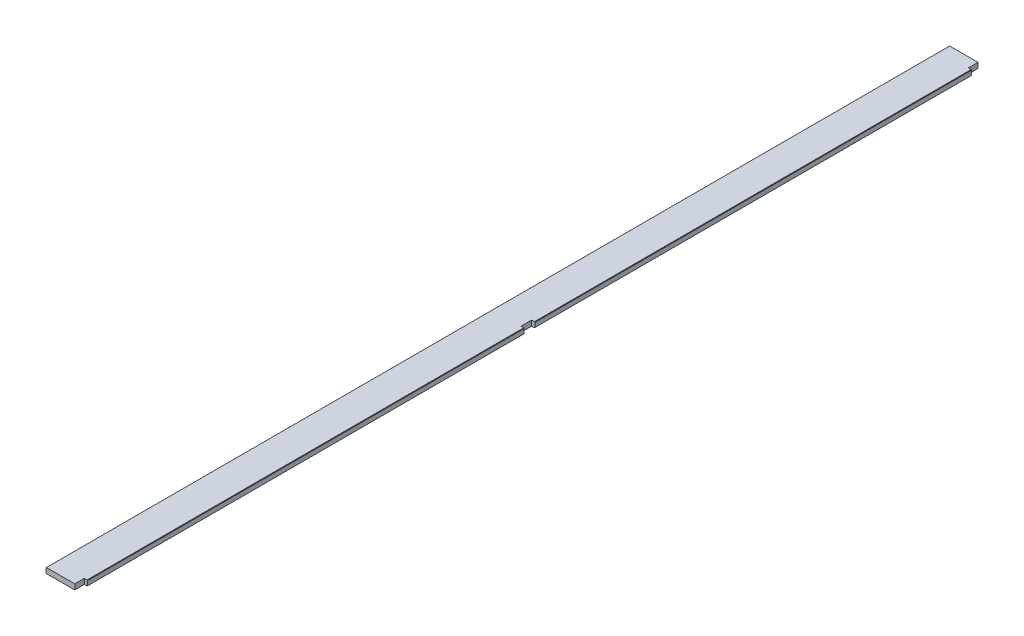
SolidWorks part; units mm, degrees
ref_plane "Спереди" through (0, 0, 0) normal (0, 0, 1) x (1, 0, 0)
ref_plane "Сверху" through (0, 0, 0) normal (0, 1, 0) x (1, 0, 0)
ref_plane "Справа" through (0, 0, 0) normal (1, 0, 0) x (0, 0, -1)
sketch "Эскиз1" plane through (0, 0, 0) normal (0, 0, 1) x (1, 0, 0)
  line L0 (-75, 10.5) -> (-73, 12.5)
  line L1 (-73, 12.5) -> (73, 12.5)
  line L2 (-75, 10.5) -> (-75, -10.5)
  line L3 (-73, -12.5) -> (73, -12.5)
  line L4 (75, 10.5) -> (75, -10.5)
  line L5 (-75, 12.5) -> (75, -12.5) construction
  line L6 (-75, -12.5) -> (75, 12.5) construction
  line L7 (-75, -10.5) -> (-73, -12.5)
  line L8 (73, -12.5) -> (75, -10.5)
  line L9 (73, 12.5) -> (75, 10.5)
  point P0 (0, 0)
  dimension "D1" = 150
  dimension "D2" = 25
extrude "Бобышка-Вытянуть1" add sketch "Эскиз1" along normal blind 4240
sketch "Эскиз2" plane through (0, 12.5, 0) normal (0, 1, 0) x (1, 0, 0)
  line L0 (73, -2120) -> (-49927, -2120) construction
  line L1 (75, 0) -> (60, 0)
  line L2 (75, 0) -> (75, -45)
  line L3 (75, -45) -> (60, -45)
  line L4 (60, 0) -> (60, -45)
  line L5 (75, -4240) -> (60, -4240)
  line L6 (75, -4240) -> (75, -4195)
  line L7 (75, -4195) -> (60, -4195)
  line L8 (60, -4240) -> (60, -4195)
  line L9 (73, -4240) -> (73, 0) construction
  line L10 (75, -4240) -> (75, 0) construction
  line L11 (75, -2145) -> (60, -2145)
  line L12 (75, -2145) -> (75, -2095)
  line L13 (75, -2095) -> (60, -2095)
  line L14 (60, -2145) -> (60, -2095)
  point P14 (73, -2120)
  dimension "D1" = 45
  dimension "D2" = 15
  dimension "D3" = 15
  dimension "D4" = 45
  dimension "D5" = 50
  dimension "D6" = 15
  dimension "D7" = 25
extrude "Вырез-Вытянуть1" cut sketch "Эскиз2" against normal through all
